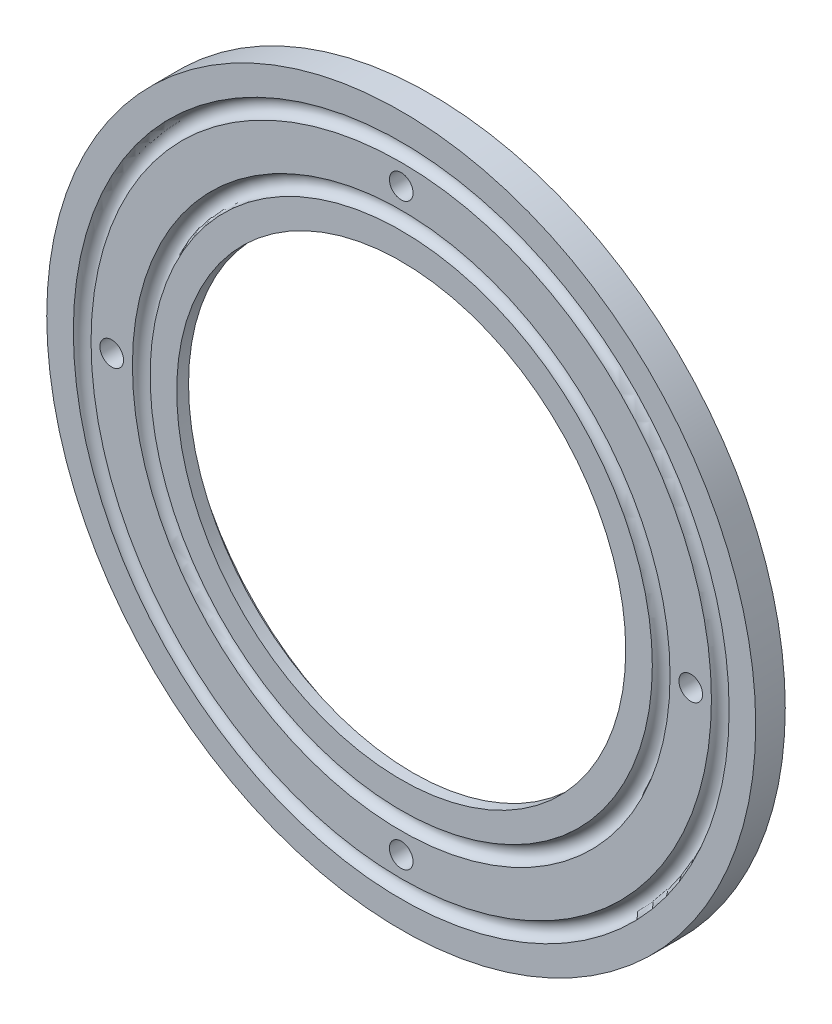
SolidWorks part; units mm, degrees
ref_plane "Front Plane" through (0, 0, 0) normal (0, 0, 1) x (1, 0, 0)
ref_plane "Top Plane" through (0, 0, 0) normal (0, 1, 0) x (1, 0, 0)
ref_plane "Right Plane" through (0, 0, 0) normal (1, 0, 0) x (0, 0, -1)
sketch "Sketch3" plane through (0, 0, 0) normal (0, 1, 0) x (1, 0, 0)
  line L0 (0, 0) -> (0, 79.4731) construction
  line L1 (0, 0) -> (38, 0) construction
  line L2 (60, 0) -> (60, 5)
  line L3 (38, 5) -> (60, 5)
  line L4 (38, 0) -> (42.5, 0)
  line L5 (45.5, 0) -> (52.5, 0)
  line L6 (38, 0) -> (38, 5)
  line L7 (55.5, 0) -> (60, 0)
  line L8 (38, 5) -> (0, 5) construction
  arc A0 (45.5, 0) -> (42.5, 0) centre (44, 0) ccw
  arc A1 (55.5, 0) -> (52.5, 0) centre (54, 0) ccw
  dimension "D5" = 6
  dimension "D6" = 5
  dimension "D2" = 6
  dimension "D1" = 60
  dimension "D3" = 44
  dimension "D4" = 54
  dimension "D7" = 38
  dimension "D8" = 5
  dimension "D10" = 6
revolve "Revolve1" add sketch "Sketch3" angle 360 about L0
sketch "Sketch4" plane through (0, 0, 0) normal (0, 0, 1) x (1, 0, 0)
  circle A0 centre (0, 0) radius 52.5 construction
  circle A1 centre (0, 0) radius 45.5 construction
  circle A2 centre (0, 0) radius 49 construction
  circle A3 centre (49, 0) radius 2
  circle A4 centre (-49, 0) radius 2
  circle A5 centre (0, 49) radius 2
  circle A6 centre (0, -49) radius 2
  dimension "D1" = 7
  dimension "D2" = 98
  dimension "D3" = 4
  dimension "D4" = 4
  dimension "D5" = 4
  dimension "D6" = 4
extrude "Cut-Extrude1" cut sketch "Sketch4" against normal blind 10
sketch "Sketch5" plane through (0, 0, -5) normal (0, 0, -1) x (-1, 0, 0)
  circle A2 centre (0, 0) radius 38
  circle A3 centre (0, 0) radius 42
  dimension "D1" = 76
  dimension "D2" = 84
extrude "Cut-Extrude2" cut sketch "Sketch5" against normal blind 3 contours A3
